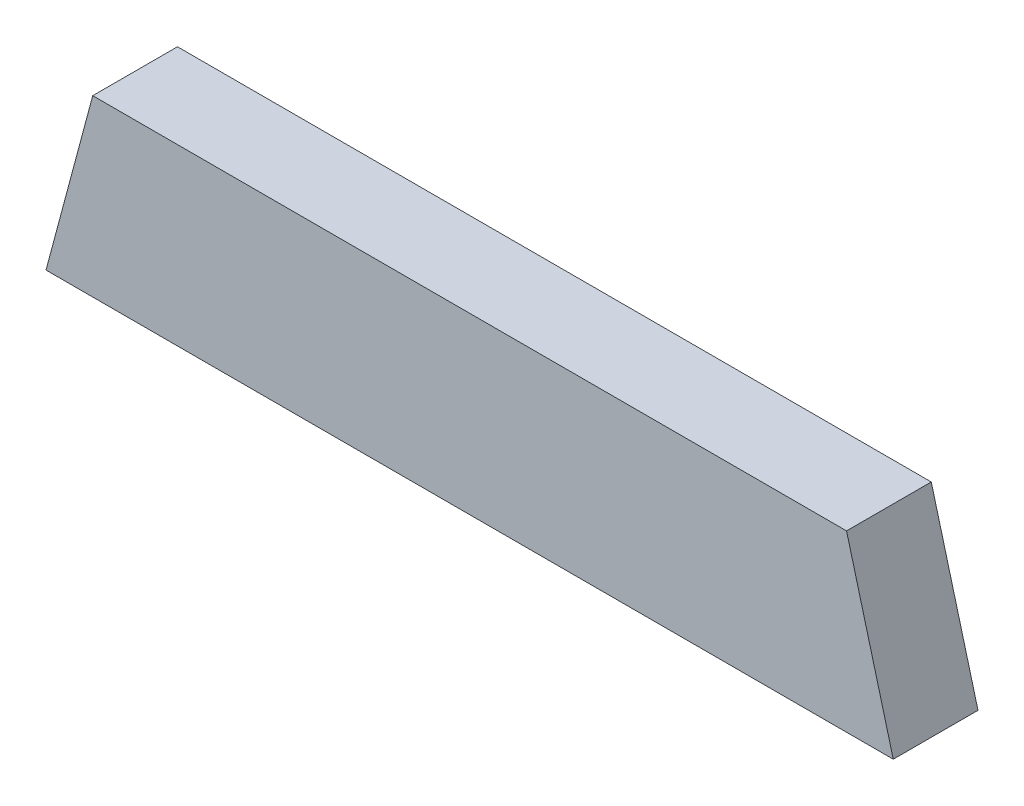
SolidWorks part; units mm, degrees
ref_plane "Front Plane" through (0, 0, 0) normal (0, 0, 1) x (1, 0, 0)
ref_plane "Top Plane" through (0, 0, 0) normal (0, 1, 0) x (1, 0, 0)
ref_plane "Right Plane" through (0, 0, 0) normal (1, 0, 0) x (0, 0, -1)
sketch "Sketch1" plane through (0, 0, 0) normal (0, 0, 1) x (1, 0, 0)
  line L0 (0, 0) -> (28.02, 104.572)
  line L1 (0, 0) -> (508, 0)
  line L2 (0, 0) -> (0, 104.572)
  line L3 (0, 104.572) -> (508, 104.572)
  line L4 (508, 0) -> (508, 104.572)
  line L5 (479.98, 104.572) -> (508, 0)
  dimension "D1" = 508
  dimension "D2" = 104.572
  dimension "D3" = 15
  dimension "D4" = 15
extrude "Boss-Extrude1" add sketch "Sketch1" along normal blind 50.8 contours L5 L3 L0 L1
